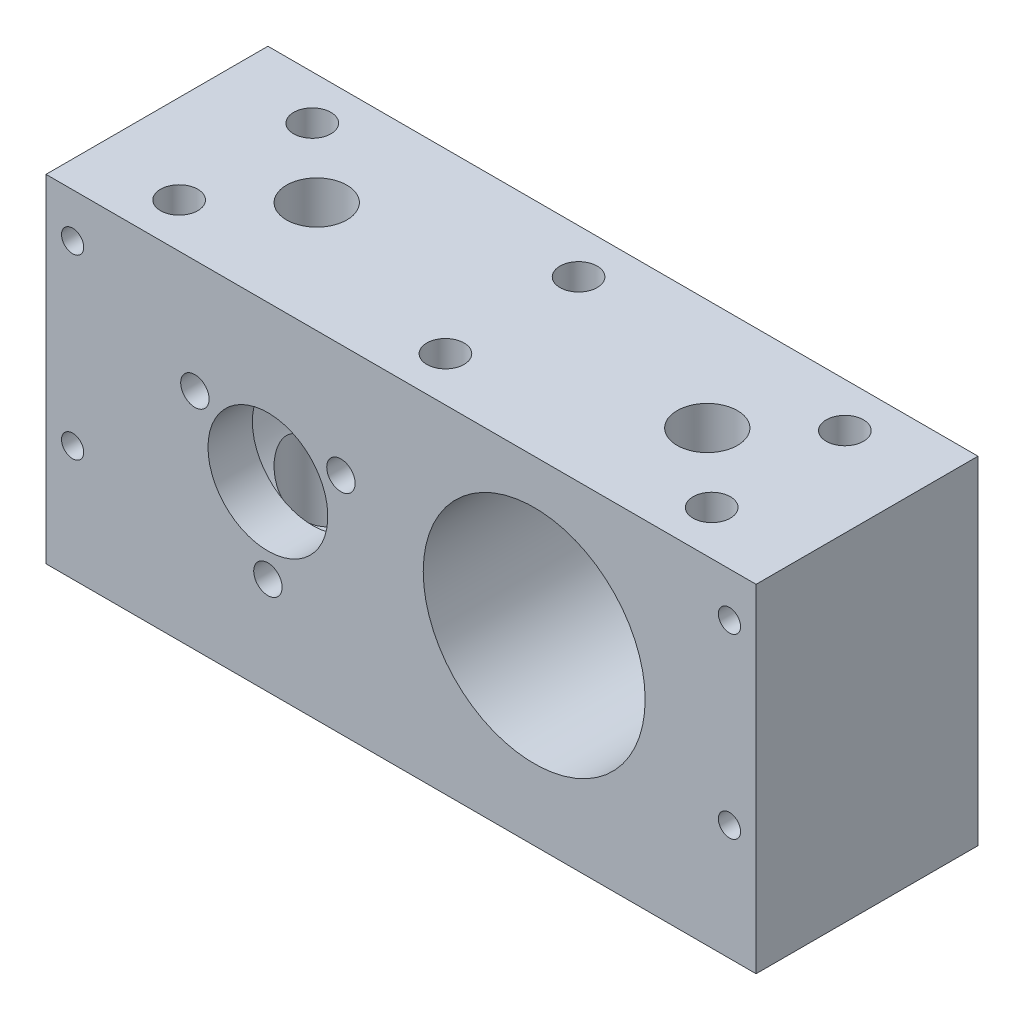
SolidWorks part; units mm, degrees
ref_plane "前视基准面" through (0, 0, 0) normal (0, 0, 1) x (1, 0, 0)
ref_plane "上视基准面" through (0, 0, 0) normal (0, 1, 0) x (1, 0, 0)
ref_plane "右视基准面" through (0, 0, 0) normal (1, 0, 0) x (0, 0, -1)
other "Configuration Table"
sketch "草图1" plane through (0, 0, 0) normal (0, 0, 1) x (1, 0, 0)
  line L1 (-35, 17.5) -> (35, 17.5)
  line L2 (-35, 17.5) -> (-35, -17.5)
  line L3 (-35, -17.5) -> (35, -17.5)
  line L4 (35, 17.5) -> (35, -17.5)
  line L5 (0, -17.5) -> (0, 17.5) construction
  line L6 (-35, 0) -> (35, 0) construction
  point P0 (0, 0)
  dimension "D1" = 70
  dimension "D2" = 35
extrude "凸台-拉伸1" add sketch "草图1" along normal blind 25
sketch "草图3" plane through (0, 0, 0) normal (0, 0, -1) x (-1, 0, 0)
  line L0 (-35, 0) -> (35, 0) construction
  line L1 (-35, -17.5) -> (-35, 17.5) construction
  line L2 (35, 17.5) -> (35, -17.5) construction
  circle A0 centre (15, 0) radius 12.5
  dimension "D1" = 25
  dimension "D2" = 20
extrude "切除-拉伸2" cut sketch "草图3" against normal blind 20
sketch "草图5" plane through (0, 0, 20) normal (0, 0, -1) x (-1, 0, 0)
  circle A0 centre (15, 0) radius 6.75
  dimension "D1" = 13.5
extrude "切除-拉伸4" cut sketch "草图5" against normal blind 5
sketch "草图6" plane through (0, 0, 20) normal (0, 0, -1) x (-1, 0, 0)
  line L0 (15, 0) -> (15, -9.5) construction
  line L1 (15, 0) -> (15, -9.5) construction
  circle A0 centre (15, 0) radius 9.5 construction
  circle A1 centre (15, -9.5) radius 1.6
  circle A2 centre (6.7728, 4.75) radius 1.6
  circle A3 centre (23.2272, 4.75) radius 1.6
  point P13 (15, 0)
  dimension "D1" = 19
  dimension "D2" = 3.2
  dimension "D3" = 0
  dimension "D4" = 3
extrude "切除-拉伸5" cut sketch "草图6" against normal blind 5
sketch "草图8" plane through (0, 0, 25) normal (0, 0, 1) x (1, 0, 0)
  line L0 (35, 0) -> (-35, 0) construction
  line L1 (35, -17.5) -> (35, 17.5) construction
  line L2 (-35, 17.5) -> (-35, -17.5) construction
  circle A0 centre (15, 0) radius 12.5
  dimension "D1" = 25
  dimension "D2" = 20
extrude "切除-拉伸6" cut sketch "草图8" against normal blind 20
sketch "草图9" plane through (0, 0, 5) normal (0, 0, 1) x (1, 0, 0)
  circle A0 centre (15, 0) radius 6.75
  dimension "D1" = 13.5
extrude "切除-拉伸7" cut sketch "草图9" against normal blind 20
sketch "草图10" plane through (0, 0, 5) normal (0, 0, 1) x (1, 0, 0)
  line L0 (15, 0) -> (24.5, 0) construction
  line L1 (15, 0) -> (15, -9.5) construction
  circle A0 centre (15, 0) radius 9.5 construction
  circle A1 centre (15, -9.5) radius 1.6
  circle A2 centre (6.7728, 4.75) radius 1.6
  circle A3 centre (23.2272, 4.75) radius 1.6
  point P12 (15, 0)
  dimension "D1" = 19
  dimension "D3" = 3.2
  dimension "D2" = 90
  dimension "D4" = 3
extrude "切除-拉伸8" cut sketch "草图10" against normal through all
sketch "草图11" plane through (0, -17.5, 0) normal (0, -1, 0) x (1, 0, 0)
  line L0 (35, 12.5) -> (-35, 12.5) construction
  line L1 (35, 25) -> (35, 0) construction
  line L2 (-35, 25) -> (-35, 0) construction
  line L3 (0, 25) -> (0, 0) construction
  line L4 (-35, 25) -> (35, 25) construction
  circle A0 centre (22, 12.5) radius 3.4
  circle A2 centre (-22, 12.5) radius 3.4
  circle A3 centre (0, 12.5) radius 30 construction
  dimension "D1" = 6.8
  dimension "D2" = 22
  dimension "D3" = 60
extrude "切除-拉伸9" cut sketch "草图11" against normal through all
sketch "草图13" plane through (0, -17.5, 0) normal (0, -1, 0) x (1, 0, 0)
  line L1 (35, 25) -> (-35, 25)
  line L2 (35, 25) -> (35, 0)
  line L3 (35, 0) -> (-35, 0)
  line L4 (-35, 25) -> (-35, 0)
  circle A0 centre (-22, 12.5) radius 3.4 construction
  circle A1 centre (22, 12.5) radius 3.4 construction
  circle A2 centre (-22, 12.5) radius 3.4
  circle A3 centre (22, 12.5) radius 3.4
extrude "凸台-拉伸3" add sketch "草图13" along normal blind 3
sketch "草图2" plane through (0, 17.5, 0) normal (0, 1, 0) x (1, 0, 0)
  line L0 (0, 0) -> (0, -25) construction
  line L1 (35, -25) -> (-35, -25) construction
  line L3 (30, -5) -> (-30, -5) construction
  line L4 (30, -5) -> (30, -20) construction
  line L5 (30, -20) -> (-30, -20) construction
  line L6 (-30, -5) -> (-30, -20) construction
  line L7 (0, -20) -> (0, -5) construction
  line L8 (30, -12.5) -> (-30, -12.5) construction
  circle A0 centre (30, -5) radius 2.1
  circle A1 centre (30, -20) radius 2.1
  circle A2 centre (-30, -5) radius 2.1
  circle A3 centre (-30, -20) radius 2.1
  point P5 (0, -12.5)
  dimension "D3" = 4.2
  dimension "D1" = 60
  dimension "D2" = 15
extrude "切除-拉伸1" cut sketch "草图2" against normal through all
sketch "草图15" plane through (-35, 0, 0) normal (-1, 0, 0) x (0, 0, 1)
  line L4 (0, 17.5) -> (0, -20.5)
  line L5 (0, -20.5) -> (25, -20.5)
  line L6 (25, -20.5) -> (25, 17.5)
  line L7 (25, 17.5) -> (0, 17.5)
  line L8 (0, 17.5) -> (0, -20.5)
  line L9 (0, -20.5) -> (25, -20.5)
  line L10 (25, -20.5) -> (25, 17.5)
  line L11 (25, 17.5) -> (0, 17.5)
  dimension "D1" = 0
extrude "凸台-拉伸4" add sketch "草图15" along normal blind 5
sketch "草图16" plane through (35, 0, 0) normal (1, 0, 0) x (0, 0, -1)
  line L4 (0, -20.5) -> (0, 17.5)
  line L5 (0, 17.5) -> (-25, 17.5)
  line L6 (-25, 17.5) -> (-25, -20.5)
  line L7 (-25, -20.5) -> (0, -20.5)
  line L8 (0, -20.5) -> (0, 17.5)
  line L9 (0, 17.5) -> (-25, 17.5)
  line L10 (-25, 17.5) -> (-25, -20.5)
  line L11 (-25, -20.5) -> (0, -20.5)
  dimension "D1" = 0
extrude "凸台-拉伸5" add sketch "草图16" along normal blind 5
sketch "草图17" plane through (0, -20.5, 0) normal (0, -1, 0) x (1, 0, 0)
  line L0 (0, 25) -> (0, 0) construction
  line L1 (40, 25) -> (-40, 25) construction
  line L2 (-40, 0) -> (40, 0) construction
  line L3 (-40, 12.5) -> (40, 12.5) construction
  line L4 (-40, 0) -> (-40, 25) construction
  line L5 (40, 25) -> (40, 0) construction
  circle A1 centre (0, 5) radius 2.1
  circle A2 centre (0, 20) radius 2.1
  dimension "D1" = 4.2
  dimension "D2" = 5
extrude "切除-拉伸11" cut sketch "草图17" against normal through all
sketch "草图18" plane through (0, 0, 0) normal (0, 0, -1) x (-1, 0, 0)
  line L0 (-37, -20.5) -> (-37, 17.5) construction
  line L1 (40, -20.5) -> (-40, -20.5) construction
  line L2 (-40, 17.5) -> (40, 17.5) construction
  line L3 (-40, -20.5) -> (-40, 17.5) construction
  circle A0 centre (-37, 12.5) radius 1.25
  circle A1 centre (-37, -7.5) radius 1.25
  dimension "D4" = 2.5
  dimension "D5" = 2.5
  dimension "D1" = 3
  dimension "D2" = 20
  dimension "D3" = 5
extrude "切除-拉伸12" cut sketch "草图18" against normal blind 5
ref_plane "基准面1" through (0, 0, 12.5) normal (0, 0, 1) x (1, 0, 0)
mirror "镜向1" about plane through (0, 0, 12.5) normal (0, 0, 1) of "切除-拉伸12"
mirror "镜向2" about plane through (0, 0, 0) normal (1, 0, 0) of "镜向1", "切除-拉伸12"
